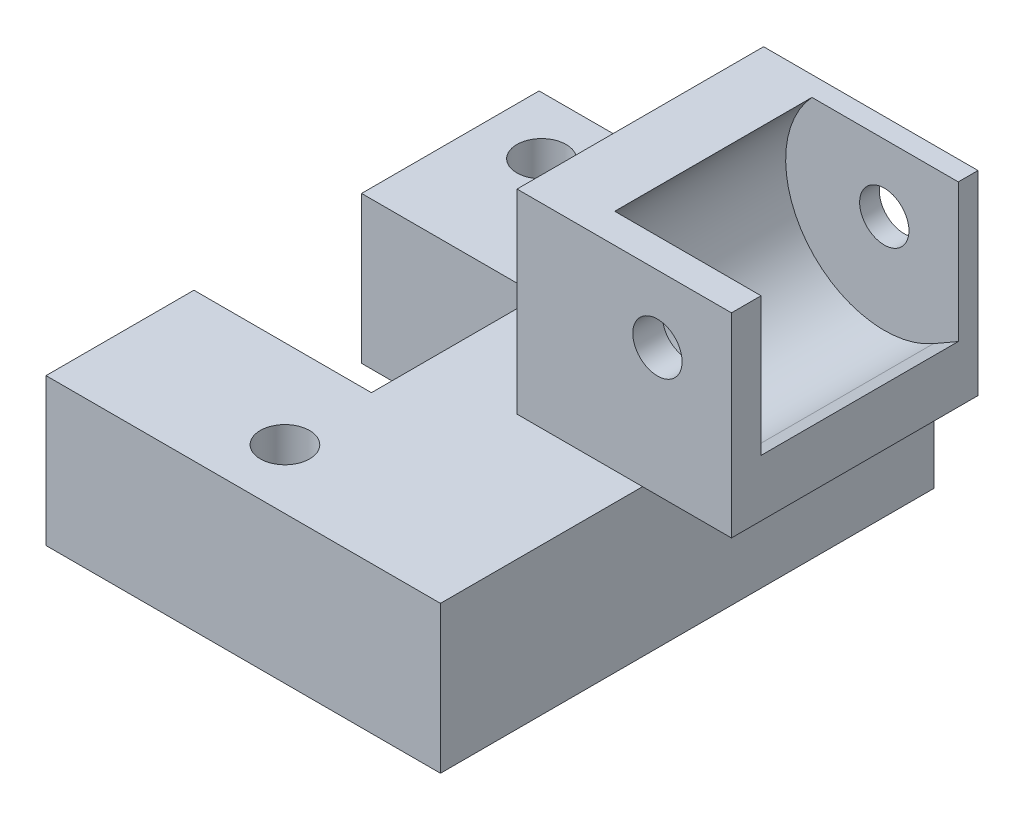
SolidWorks part; units mm, degrees
ref_plane "Front Plane" through (0, 0, 0) normal (0, 0, 1) x (1, 0, 0)
ref_plane "Top Plane" through (0, 0, 0) normal (0, 1, 0) x (1, 0, 0)
ref_plane "Right Plane" through (0, 0, 0) normal (1, 0, 0) x (0, 0, -1)
sketch "Sketch1" plane through (0, 0, 0) normal (0, 0, 1) x (1, 0, 0)
  line L0 (-527.7276, 348.6336) -> (-500.1158, 348.6336)
  line L1 (-500.1158, 348.6336) -> (-500.1158, 323.526)
  line L2 (-500.1158, 323.526) -> (-527.7276, 323.526)
  line L3 (-527.7276, 323.526) -> (-527.7276, 348.6336)
  line L4 (-471.0414, 347.5416) -> (-503.3159, 328.9895) construction
  line L5 (-471.0414, 347.5416) -> (-503.3159, 328.9895)
  arc A0 (-508.6898, 327.336) -> (-503.3159, 328.9895) centre (-509.645, 340) ccw construction
  arc A1 (-515.9742, 351.0105) -> (-520.1076, 347.199) centre (-509.645, 340) ccw construction
  arc A2 (-520.1076, 347.199) -> (-508.6898, 327.336) centre (-509.645, 340) ccw construction
  arc A3 (-508.6898, 327.336) -> (-503.3159, 328.9895) centre (-509.645, 340) ccw
  arc A4 (-515.9742, 351.0105) -> (-520.1076, 347.199) centre (-509.645, 340) ccw
  arc A5 (-520.1076, 347.199) -> (-508.6898, 327.336) centre (-509.645, 340) ccw
  dimension "D1" = 3.81
  dimension "D2" = 7.62
  dimension "D3" = 25.1076
  dimension "D4" = 27.6118
extrude "Boss-Extrude1" add sketch "Sketch1" against normal blind 27.94 contours A5 A4 L0 L3 L2 L1 L5 A3
sketch "Sketch2" plane through (0, 0, -25.4) normal (0, 0, -1) x (-1, 0, 0)
  line L0 (500.1158, 330.829) -> (500.1158, 348.6336)
  line L1 (500.1158, 348.6336) -> (518.9591, 348.6336)
  line L2 (500.1158, 330.829) -> (503.3159, 328.9895) construction
  line L3 (500.1158, 330.829) -> (503.3159, 328.9895)
  arc A0 (503.3159, 328.9895) -> (518.9591, 348.6336) centre (509.645, 340) ccw construction
  arc A1 (503.3159, 328.9895) -> (518.9591, 348.6336) centre (509.645, 340) ccw
  circle A2 centre (509.645, 340) radius 3.175
  dimension "D1" = 6.35
extrude "Boss-Extrude2" add sketch "Sketch2" along normal up to surface (2.54 mm away) up to face at (-514.4007, 332.9024, -27.94)
sketch "Sketch3" plane through (0, 0, 0) normal (0, 0, 1) x (1, 0, 0)
  line L0 (-527.7276, 348.6336) -> (-500.1158, 348.6336)
  line L1 (-500.1158, 348.6336) -> (-500.1158, 323.526)
  line L2 (-500.1158, 323.526) -> (-527.7276, 323.526)
  line L3 (-527.7276, 323.526) -> (-527.7276, 348.6336)
  circle A0 centre (-509.645, 340) radius 3.175
  dimension "D1" = 6.35
extrude "Boss-Extrude3" add sketch "Sketch3" along normal blind 3.81 contours L3 L0 L1 L2 | A0
ref_plane "Plane1" through (0, 323.526, 0) normal (0, 1, 0) x (1, 0, 0)
sketch "Sketch4" plane through (0, 323.526, 0) normal (0, 1, 0) x (1, 0, 0)
  line L1 (-562.3598, 33.6602) -> (-511.5598, 33.7024)
  line L2 (-562.3598, 33.6602) -> (-562.3598, -29.8398)
  line L3 (-562.3598, -29.8398) -> (-511.5598, -29.8398)
  line L4 (-511.5598, 33.7024) -> (-511.5598, -29.8398)
  circle A0 centre (-539.2691, -22.1596) radius 3.175
  circle A1 centre (-554.6451, 26.2575) radius 3.175
  dimension "D5" = 50.8
  dimension "D9" = 6.35
  dimension "D10" = 6.35
  dimension "D2" = 63.5
  dimension "D3" = 63.5422
  dimension "D4" = 50.8
  dimension "D6" = 7.7147
  dimension "D7" = 7.6801
  dimension "D8" = 23.0907
extrude "Boss-Extrude4" add sketch "Sketch4" against normal up to surface (18.9546 mm away)
sketch "Sketch5" plane through (0, 323.526, 0) normal (0, 1, 0) x (1, 0, 0)
  line L0 (-562.3598, 10.8002) -> (-539.4998, 10.8002)
  line L1 (-562.3598, 33.6602) -> (-562.3598, -29.8398) construction
  line L2 (-539.4998, 10.8002) -> (-539.4998, -10.7898)
  line L3 (-539.4998, -10.7898) -> (-562.3598, -10.7898)
  line L4 (-562.3598, -10.7898) -> (-562.3598, 10.8002)
  line L7 (-562.3598, -29.8398) -> (-511.5598, -29.8398) construction
  dimension "D1" = 22.86
  dimension "D2" = 21.59
  dimension "D3" = 19.05
extrude "Cut-Extrude1" cut sketch "Sketch5" against normal through all
